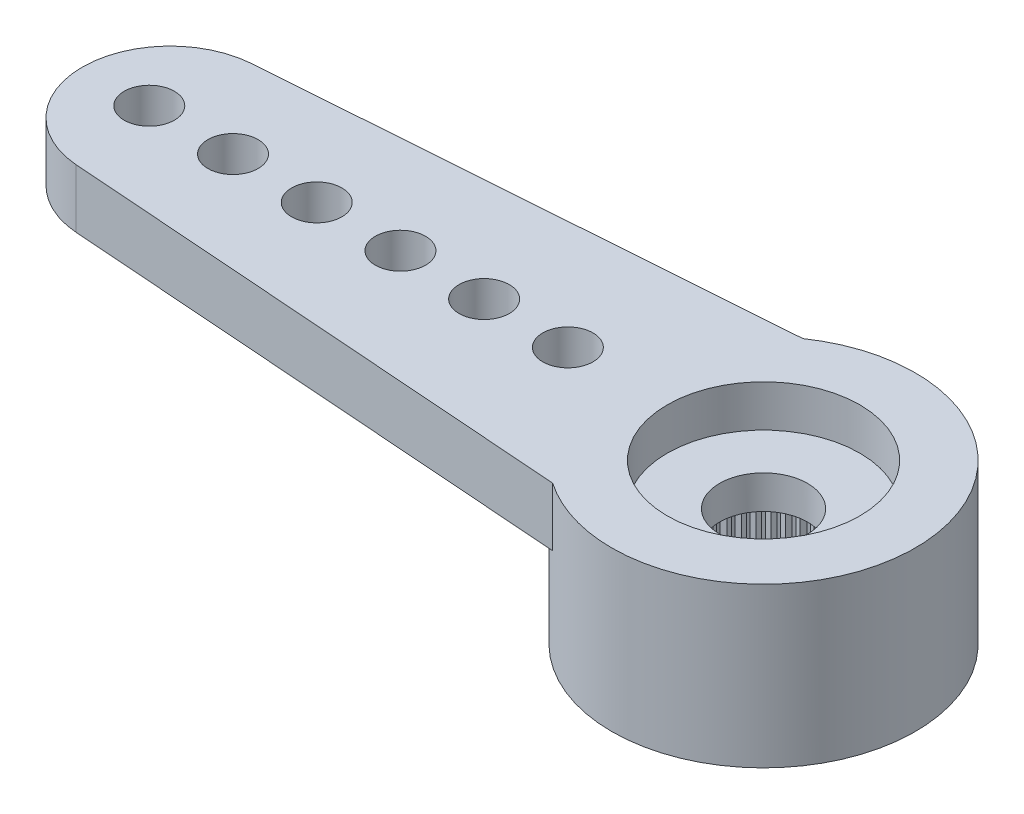
SolidWorks part; units mm, degrees
material "PVC Rígido"
ref_plane "Plano frontal" through (0, 0, 0) normal (0, 0, 1) x (1, 0, 0)
ref_plane "Plano superior" through (0, 0, 0) normal (0, 1, 0) x (1, 0, 0)
ref_plane "Plano direito" through (0, 0, 0) normal (1, 0, 0) x (0, 0, -1)
sketch "Esboço1" plane through (0, 0, 0) normal (0, 1, 0) x (1, 0, 0)
  line L0 (0, 0) -> (-14.175, 0) construction
  line L1 (-14.3278, 2.0944) -> (-2.0495, 2.99)
  line L2 (-2.0495, -2.99) -> (-14.3278, -2.0944)
  arc A0 (-2.0495, -2.99) -> (-2.0495, 2.99) centre (0, 0) ccw
  arc A1 (-14.3278, 2.0944) -> (-14.3278, -2.0944) centre (-14.175, 0) ccw
  dimension "D1" = 7.25
  dimension "D2" = 4.2
  dimension "D3" = 19.9
  dimension "D4" = 5.98
extrude "Ressalto-extrusão1" add sketch "Esboço1" against normal blind 1.4
sketch "Esboço2" plane through (0, -1.4, 0) normal (0, -1, 0) x (1, 0, 0)
  arc A0 (-2.0495, -2.99) -> (-2.0495, 2.99) centre (0, 0) ccw construction
  circle A1 centre (0, 0) radius 3.625
extrude "Ressalto-extrusão2" add sketch "Esboço2" along normal offset from surface (2.4 mm away) 3.8 up to face at (-7.2568, 0, 0)
hole_wizard "Furo4" positions "Esboço9" profile "Esboço10" legacy end condition through all
sketch "Esboço9" plane through (0, 0, 0) normal (0, 1, 0) x (1, 0, 0)
  line L1 (-14.675, 0) -> (0, 0) construction
  arc A2 (-14.3278, 2.0944) -> (-14.3278, -2.0944) centre (-14.175, 0) ccw construction
  point P0 (-14.675, 0)
  point P19 (-16.275, 0)
  dimension "D1" = 1.6
sketch "Esboço10" plane through (-14.675, 0, 0) normal (1, 0, 0) x (0, 0, 1)
  line L0 (0, 0) -> (0, 3.8)
  line L1 (0, 3.8) -> (0.6, 3.8)
  line L2 (0.6, 3.8) -> (0.6, 0)
  line L3 (0.6, 0) -> (0, 0)
  line L4 (0, 110) -> (0, -10) construction
  dimension "Diameter" = 1.2
  dimension "Depth" = 3.8
pattern_linear "Padrão linear1" count 6 spacing 2 along (1, 0, 0) of "Furo4"
hole_wizard "Furo1" positions "Esboço3" profile "Esboço4" legacy
sketch "Esboço3" plane through (0, -3.8, 0) normal (0, -1, 0) x (-1, 0, 0)
  point P0 (0, 0)
sketch "Esboço4" plane through (0, -3.8, 0) normal (1, 0, 0) x (0, 0, -1)
  line L0 (0, 0) -> (0, 2)
  line L1 (0, 2) -> (2.475, 2)
  line L2 (2.475, 2) -> (2.475, 0)
  line L3 (2.475, 0) -> (0, 0)
  line L4 (0, 110) -> (0, -10) construction
  dimension "Diameter" = 4.95
  dimension "Depth" = 2
hole_wizard "Furo2" positions "Esboço5" profile "Esboço6" legacy
sketch "Esboço5" plane through (0, 0, 0) normal (0, 1, 0) x (1, 0, 0)
  point P0 (0, 0)
sketch "Esboço6" plane through (0, 0, 0) normal (1, 0, 0) x (0, 0, 1)
  line L0 (0, 0) -> (0, 1)
  line L1 (0, 1) -> (2.3, 1)
  line L2 (2.3, 1) -> (2.3, 0)
  line L3 (2.3, 0) -> (0, 0)
  line L4 (0, 110) -> (0, -10) construction
  dimension "Diameter" = 4.6
  dimension "Depth" = 1
hole_wizard "Furo3" positions "Esboço7" profile "Esboço8" legacy end condition through all
sketch "Esboço7" plane through (0, 0, 0) normal (0, 1, 0) x (1, 0, 0)
  point P0 (0, 0)
sketch "Esboço8" plane through (0, 0, 0) normal (1, 0, 0) x (0, 0, 1)
  line L0 (0, 0) -> (0, 3.8)
  line L1 (0, 3.8) -> (1.05, 3.8)
  line L2 (1.05, 3.8) -> (1.05, 0)
  line L3 (1.05, 0) -> (0, 0)
  line L4 (0, 110) -> (0, -10) construction
  dimension "Diameter" = 2.1
  dimension "Depth" = 3.8
sketch "Esboço11" plane through (0, -3.8, 0) normal (0, -1, 0) x (1, 0, 0)
  line L0 (-0.0981, 2.4731) -> (0, 2.375)
  line L1 (0, 2.375) -> (0.0981, 2.4731)
  line L2 (0, 0) -> (0, 2.475) construction
  circle A0 centre (0, 0) radius 2.375 construction
  circle A1 centre (0, 0) radius 2.475
  arc A2 (0.0981, 2.4731) -> (-0.0981, 2.4731) centre (0, 0) ccw
  dimension "D3" = 4.75
  dimension "D2" = 0.1
  dimension "D1" = 0
extrude "Ressalto-extrusão3" add sketch "Esboço11" against normal up to surface (2 mm away) up to face at (0, -1.8, 1.05)
pattern_circular "PadrãoCircular1" count 60 over 360 about axis through (0, 0, 0) along (0, 1, 0) of "Ressalto-extrusão3"
